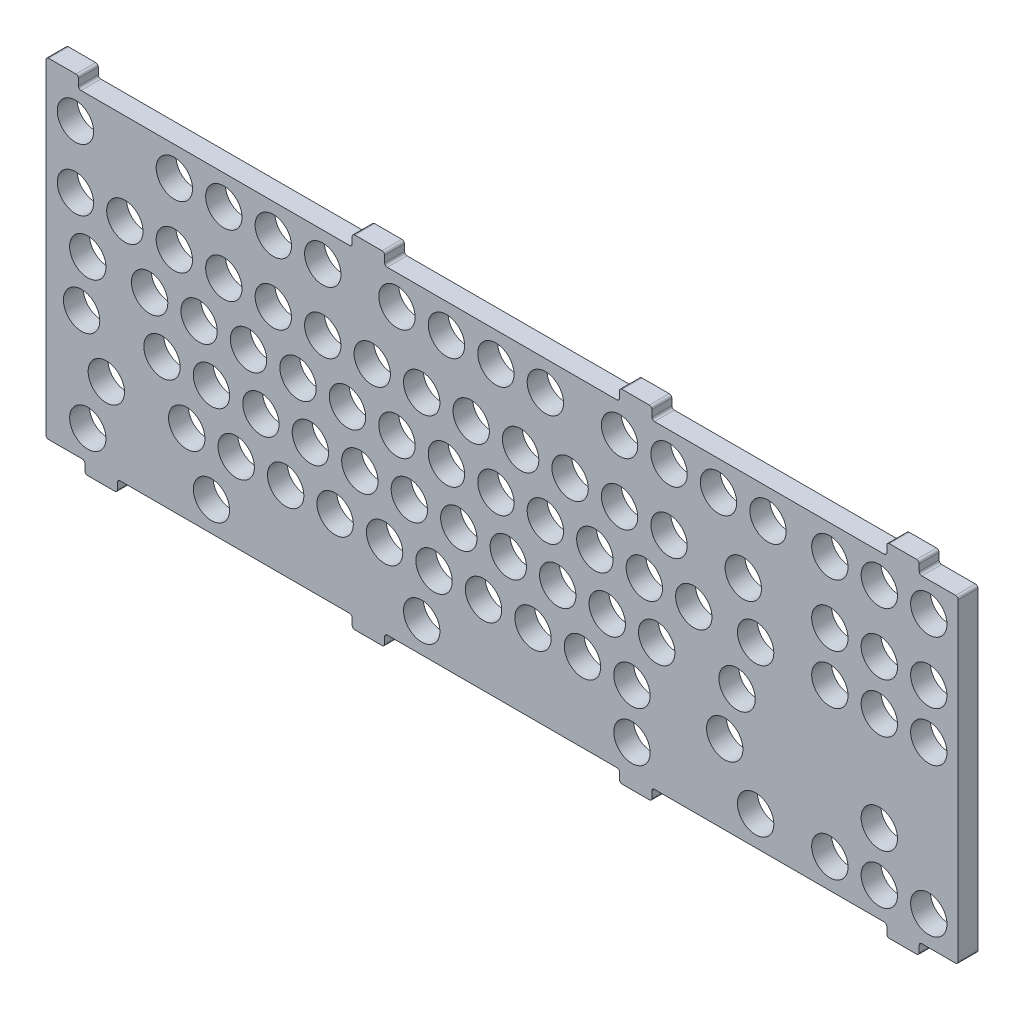
SolidWorks part; units mm, degrees
ref_plane "Front Plane" through (0, 0, 0) normal (0, 0, 1) x (1, 0, 0)
ref_plane "Top Plane" through (0, 0, 0) normal (0, 1, 0) x (1, 0, 0)
ref_plane "Right Plane" through (0, 0, 0) normal (1, 0, 0) x (0, 0, -1)
sketch "Sketch1" plane through (0, 0, 0) normal (0, 0, 1) x (1, 0, 0)
  line L0 (-164.1313, 65.8312) -> (-174.6313, 65.8312)
  line L1 (-163.1313, 62.3312) -> (-163.1312, 64.8312)
  line L2 (-58.7104, 61.3312) -> (-162.1313, 61.3312)
  line L3 (-57.7104, 64.8312) -> (-57.7104, 62.3312)
  line L4 (-45.2104, 62.3312) -> (-45.2104, 64.8312)
  line L5 (44.2104, 61.3312) -> (-44.2104, 61.3312)
  line L6 (45.2104, 64.8312) -> (45.2104, 62.3312)
  line L7 (56.7104, 65.8312) -> (46.2104, 65.8312)
  line L8 (57.7104, 62.3312) -> (57.7104, 64.8312)
  line L9 (147.1312, 61.3312) -> (58.7104, 61.3312)
  line L10 (148.1312, 64.8312) -> (148.1312, 62.3312)
  line L11 (159.6312, 65.8312) -> (149.1312, 65.8312)
  line L12 (160.6312, 62.3312) -> (160.6312, 64.8312)
  line L13 (174.6313, 61.3312) -> (161.6312, 61.3312)
  line L14 (175.6313, -60.3312) -> (175.6313, 60.3312)
  line L15 (161.6312, -61.3312) -> (174.6313, -61.3312)
  line L16 (160.6312, -64.8312) -> (160.6312, -62.3312)
  line L17 (149.1312, -65.8312) -> (159.6312, -65.8312)
  line L18 (148.1312, -62.3312) -> (148.1312, -64.8312)
  line L19 (58.7104, -61.3312) -> (147.1312, -61.3312)
  line L20 (57.7104, -64.8312) -> (57.7104, -62.3312)
  line L21 (46.2104, -65.8312) -> (56.7104, -65.8312)
  line L22 (45.2104, -62.3312) -> (45.2104, -64.8312)
  line L23 (-44.2104, -61.3312) -> (44.2104, -61.3312)
  line L24 (-45.2104, -64.8312) -> (-45.2104, -62.3312)
  line L25 (-56.7104, -65.8312) -> (-46.2104, -65.8312)
  line L26 (-57.7104, -62.3312) -> (-57.7104, -64.8312)
  line L27 (-147.1313, -61.3312) -> (-58.7104, -61.3312)
  line L28 (-148.1313, -64.8312) -> (-148.1313, -62.3312)
  line L29 (-159.6313, -65.8312) -> (-149.1313, -65.8312)
  line L30 (-160.6313, -62.3312) -> (-160.6313, -64.8312)
  line L31 (-174.6313, -61.3312) -> (-161.6313, -61.3312)
  line L32 (-175.6313, 64.8312) -> (-175.6313, -60.3312)
  line L33 (-46.2104, 65.8312) -> (-56.7104, 65.8312)
  arc A0 (-163.1312, 64.8312) -> (-164.1313, 65.8312) centre (-164.1313, 64.8312) ccw
  arc A1 (-163.1313, 62.3312) -> (-162.1313, 61.3312) centre (-162.1313, 62.3312) ccw
  arc A2 (-58.7104, 61.3312) -> (-57.7104, 62.3312) centre (-58.7104, 62.3312) ccw
  arc A3 (-56.7104, 65.8312) -> (-57.7104, 64.8312) centre (-56.7104, 64.8312) ccw
  arc A4 (-45.2104, 64.8312) -> (-46.2104, 65.8312) centre (-46.2104, 64.8312) ccw
  arc A5 (-45.2104, 62.3312) -> (-44.2104, 61.3312) centre (-44.2104, 62.3312) ccw
  arc A6 (44.2104, 61.3312) -> (45.2104, 62.3312) centre (44.2104, 62.3312) ccw
  arc A7 (46.2104, 65.8312) -> (45.2104, 64.8312) centre (46.2104, 64.8312) ccw
  arc A8 (57.7104, 64.8312) -> (56.7104, 65.8312) centre (56.7104, 64.8312) ccw
  arc A9 (57.7104, 62.3312) -> (58.7104, 61.3312) centre (58.7104, 62.3312) ccw
  arc A10 (147.1312, 61.3312) -> (148.1312, 62.3312) centre (147.1312, 62.3312) ccw
  arc A11 (149.1312, 65.8312) -> (148.1312, 64.8312) centre (149.1312, 64.8312) ccw
  arc A12 (160.6312, 62.3312) -> (161.6312, 61.3312) centre (161.6312, 62.3312) ccw
  arc A13 (175.6313, 60.3312) -> (174.6313, 61.3312) centre (174.6313, 60.3312) ccw
  arc A14 (174.6313, -61.3312) -> (175.6313, -60.3312) centre (174.6313, -60.3312) ccw
  arc A15 (161.6312, -61.3312) -> (160.6312, -62.3312) centre (161.6312, -62.3312) ccw
  arc A16 (159.6312, -65.8312) -> (160.6312, -64.8312) centre (159.6312, -64.8312) ccw
  arc A17 (148.1312, -64.8312) -> (149.1312, -65.8312) centre (149.1312, -64.8312) ccw
  arc A18 (148.1312, -62.3312) -> (147.1312, -61.3312) centre (147.1312, -62.3312) ccw
  arc A19 (58.7104, -61.3312) -> (57.7104, -62.3312) centre (58.7104, -62.3312) ccw
  arc A20 (56.7104, -65.8312) -> (57.7104, -64.8312) centre (56.7104, -64.8312) ccw
  arc A21 (45.2104, -64.8312) -> (46.2104, -65.8312) centre (46.2104, -64.8312) ccw
  arc A22 (45.2104, -62.3312) -> (44.2104, -61.3312) centre (44.2104, -62.3312) ccw
  arc A23 (-44.2104, -61.3312) -> (-45.2104, -62.3312) centre (-44.2104, -62.3312) ccw
  arc A24 (-46.2104, -65.8312) -> (-45.2104, -64.8312) centre (-46.2104, -64.8312) ccw
  arc A25 (-57.7104, -64.8312) -> (-56.7104, -65.8312) centre (-56.7104, -64.8312) ccw
  arc A26 (-57.7104, -62.3312) -> (-58.7104, -61.3312) centre (-58.7104, -62.3312) ccw
  arc A27 (-147.1313, -61.3312) -> (-148.1313, -62.3312) centre (-147.1313, -62.3312) ccw
  arc A28 (-149.1313, -65.8312) -> (-148.1313, -64.8312) centre (-149.1313, -64.8312) ccw
  arc A29 (-160.6313, -64.8312) -> (-159.6313, -65.8312) centre (-159.6313, -64.8312) ccw
  arc A30 (-160.6313, -62.3312) -> (-161.6313, -61.3312) centre (-161.6313, -62.3312) ccw
  arc A31 (-175.6313, -60.3312) -> (-174.6313, -61.3312) centre (-174.6313, -60.3312) ccw
  arc A32 (-174.6313, 65.8312) -> (-175.6313, 64.8312) centre (-174.6313, 64.8312) ccw
  arc A33 (11.9069, -37.9562) -> (11.9069, -23.9554) centre (11.9069, -30.9558) ccw
  arc A34 (11.9069, -23.9554) -> (11.9069, -37.9562) centre (11.9069, -30.9558) ccw
  arc A35 (50.0069, -57.0062) -> (50.0069, -43.0054) centre (50.0069, -50.0058) ccw
  arc A36 (50.0069, -43.0054) -> (50.0069, -57.0062) centre (50.0069, -50.0058) ccw
  arc A37 (40.4819, -18.906) -> (40.4819, -4.9054) centre (40.4819, -11.9057) ccw
  arc A38 (40.4819, -4.9054) -> (40.4819, -18.906) centre (40.4819, -11.9057) ccw
  arc A39 (2.3819, -18.906) -> (2.3819, -4.9054) centre (2.3819, -11.9057) ccw
  arc A40 (2.3819, -4.9054) -> (2.3819, -18.906) centre (2.3819, -11.9057) ccw
  arc A41 (-35.7196, -18.906) -> (-35.7196, -4.9054) centre (-35.7196, -11.9057) ccw
  arc A42 (-35.7196, -4.9054) -> (-35.7196, -18.906) centre (-35.7196, -11.9057) ccw
  arc A43 (-45.2431, -37.9562) -> (-45.2431, -23.9554) centre (-45.2431, -30.9558) ccw
  arc A44 (-45.2431, -23.9554) -> (-45.2431, -37.9562) centre (-45.2431, -30.9558) ccw
  arc A45 (-54.7696, -18.906) -> (-54.7696, -4.9054) centre (-54.7696, -11.9057) ccw
  arc A46 (-54.7696, -4.9054) -> (-54.7696, -18.906) centre (-54.7696, -11.9057) ccw
  arc A47 (-64.2946, -37.9562) -> (-64.2946, -23.9554) centre (-64.2946, -30.9558) ccw
  arc A48 (-64.2946, -23.9554) -> (-64.2946, -37.9562) centre (-64.2946, -30.9558) ccw
  arc A49 (-102.3933, -37.9562) -> (-102.3933, -23.9554) centre (-102.3933, -30.9558) ccw
  arc A50 (-102.3933, -23.9554) -> (-102.3933, -37.9562) centre (-102.3933, -30.9558) ccw
  arc A51 (-111.9197, -18.906) -> (-111.9197, -4.9054) centre (-111.9197, -11.9057) ccw
  arc A52 (-111.9197, -4.9054) -> (-111.9197, -18.906) centre (-111.9197, -11.9057) ccw
  arc A53 (-121.4433, -37.9562) -> (-121.4433, -23.9554) centre (-121.4433, -30.9558) ccw
  arc A54 (-121.4433, -23.9554) -> (-121.4433, -37.9562) centre (-121.4433, -30.9558) ccw
  arc A55 (-159.5432, -57.0062) -> (-159.5432, -43.0054) centre (-159.5432, -50.0058) ccw
  arc A56 (-159.5432, -43.0054) -> (-159.5432, -57.0062) centre (-159.5432, -50.0058) ccw
  arc A57 (-161.9252, -18.906) -> (-161.9252, -4.9054) centre (-161.9252, -11.9057) ccw
  arc A58 (-161.9252, -4.9054) -> (-161.9252, -18.906) centre (-161.9252, -11.9057) ccw
  arc A59 (90.4879, -18.906) -> (90.4879, -4.9054) centre (90.4879, -11.9057) ccw
  arc A60 (90.4879, -4.9054) -> (90.4879, -18.906) centre (90.4879, -11.9057) ccw
  arc A61 (97.6319, -57.0062) -> (97.6319, -43.0054) centre (97.6319, -50.0058) ccw
  arc A62 (97.6319, -43.0054) -> (97.6319, -57.0062) centre (97.6319, -50.0058) ccw
  arc A63 (145.2569, -37.9562) -> (145.2569, -23.9554) centre (145.2569, -30.9558) ccw
  arc A64 (145.2569, -23.9554) -> (145.2569, -37.9562) centre (145.2569, -30.9558) ccw
  arc A65 (145.2569, -57.0062) -> (145.2569, -43.0054) centre (145.2569, -50.0058) ccw
  arc A66 (145.2569, -43.0054) -> (145.2569, -57.0062) centre (145.2569, -50.0058) ccw
  arc A67 (145.2569, 0.144) -> (145.2569, 14.1446) centre (145.2569, 7.1443) ccw
  arc A68 (145.2569, 14.1446) -> (145.2569, 0.144) centre (145.2569, 7.1443) ccw
  arc A69 (97.6319, 0.144) -> (97.6319, 14.1446) centre (97.6319, 7.1443) ccw
  arc A70 (97.6319, 14.1446) -> (97.6319, 0.144) centre (97.6319, 7.1443) ccw
  arc A71 (126.2069, 19.194) -> (126.2069, 33.1946) centre (126.2069, 26.1943) ccw
  arc A72 (126.2069, 33.1946) -> (126.2069, 19.194) centre (126.2069, 26.1943) ccw
  arc A73 (164.3069, 19.194) -> (164.3069, 33.1946) centre (164.3069, 26.1943) ccw
  arc A74 (164.3069, 33.1946) -> (164.3069, 19.194) centre (164.3069, 26.1943) ccw
  arc A75 (145.2569, 43.0062) -> (145.2569, 57.0062) centre (145.2569, 50.0062) ccw
  arc A76 (145.2569, 57.0062) -> (145.2569, 43.0062) centre (145.2569, 50.0062) ccw
  arc A77 (102.3934, 43.0062) -> (102.3934, 57.0062) centre (102.3934, 50.0062) ccw
  arc A78 (102.3934, 57.0062) -> (102.3934, 43.0062) centre (102.3934, 50.0062) ccw
  arc A79 (73.8184, 0.144) -> (73.8184, 14.1446) centre (73.8184, 7.1443) ccw
  arc A80 (73.8184, 14.1446) -> (73.8184, 0.144) centre (73.8184, 7.1443) ccw
  arc A81 (35.7184, 0.1315) -> (35.7184, 14.1571) centre (35.7184, 7.1443) ccw
  arc A82 (35.7184, 14.1571) -> (35.7184, 0.1315) centre (35.7184, 7.1443) ccw
  arc A83 (-2.3816, 0.144) -> (-2.3816, 14.1446) centre (-2.3816, 7.1443) ccw
  arc A84 (-2.3816, 14.1446) -> (-2.3816, 0.144) centre (-2.3816, 7.1443) ccw
  arc A85 (26.1934, 19.194) -> (26.1934, 33.1946) centre (26.1934, 26.1943) ccw
  arc A86 (26.1934, 33.1946) -> (26.1934, 19.194) centre (26.1934, 26.1943) ccw
  arc A87 (64.2934, 19.194) -> (64.2934, 33.1946) centre (64.2934, 26.1943) ccw
  arc A88 (64.2934, 33.1946) -> (64.2934, 19.194) centre (64.2934, 26.1943) ccw
  arc A89 (45.2434, 43.0062) -> (45.2434, 57.0062) centre (45.2434, 50.0062) ccw
  arc A90 (45.2434, 57.0062) -> (45.2434, 43.0062) centre (45.2434, 50.0062) ccw
  arc A91 (-2.3816, 43.0062) -> (-2.3816, 57.0062) centre (-2.3816, 50.0062) ccw
  arc A92 (-2.3816, 57.0062) -> (-2.3816, 43.0062) centre (-2.3816, 50.0062) ccw
  arc A93 (-159.5432, 0.144) -> (-159.5432, 14.1446) centre (-159.5432, 7.1443) ccw
  arc A94 (-159.5432, 14.1446) -> (-159.5432, 0.144) centre (-159.5432, 7.1443) ccw
  arc A95 (-21.4316, 0.144) -> (-21.4316, 14.1446) centre (-21.4316, 7.1443) ccw
  arc A96 (-21.4316, 14.1446) -> (-21.4316, 0.144) centre (-21.4316, 7.1443) ccw
  arc A97 (-59.5316, 0.144) -> (-59.5316, 14.1446) centre (-59.5316, 7.1443) ccw
  arc A98 (-59.5316, 14.1446) -> (-59.5316, 0.144) centre (-59.5316, 7.1443) ccw
  arc A99 (-97.6315, 0.144) -> (-97.6315, 14.1446) centre (-97.6315, 7.1443) ccw
  arc A100 (-97.6315, 14.1446) -> (-97.6315, 0.144) centre (-97.6315, 7.1443) ccw
  arc A101 (-135.7315, 0.144) -> (-135.7315, 14.1446) centre (-135.7315, 7.1443) ccw
  arc A102 (-135.7315, 14.1446) -> (-135.7315, 0.144) centre (-135.7315, 7.1443) ccw
  arc A103 (-50.0066, 19.194) -> (-50.0066, 33.1946) centre (-50.0066, 26.1943) ccw
  arc A104 (-50.0066, 33.1946) -> (-50.0066, 19.194) centre (-50.0066, 26.1943) ccw
  arc A105 (-88.1065, 19.194) -> (-88.1065, 33.1946) centre (-88.1065, 26.1943) ccw
  arc A106 (-88.1065, 33.1946) -> (-88.1065, 19.194) centre (-88.1065, 26.1943) ccw
  arc A107 (-126.2065, 19.194) -> (-126.2065, 33.1946) centre (-126.2065, 26.1943) ccw
  arc A108 (-126.2065, 33.1946) -> (-126.2065, 19.194) centre (-126.2065, 26.1943) ccw
  arc A109 (-21.4316, 43.0062) -> (-21.4316, 57.0062) centre (-21.4316, 50.0062) ccw
  arc A110 (-21.4316, 57.0062) -> (-21.4316, 43.0062) centre (-21.4316, 50.0062) ccw
  arc A111 (-69.0565, 43.0062) -> (-69.0565, 57.0062) centre (-69.0565, 50.0062) ccw
  arc A112 (-69.0565, 57.0062) -> (-69.0565, 43.0062) centre (-69.0565, 50.0062) ccw
  arc A113 (-107.1565, 43.0062) -> (-107.1565, 57.0062) centre (-107.1565, 50.0062) ccw
  arc A114 (-107.1565, 57.0062) -> (-107.1565, 43.0062) centre (-107.1565, 50.0062) ccw
  arc A115 (-164.3064, 43.0062) -> (-164.3064, 57.0062) centre (-164.3064, 50.0062) ccw
  arc A116 (-164.3064, 57.0062) -> (-164.3064, 43.0062) centre (-164.3064, 50.0062) ccw
  arc A117 (-126.2065, 43.0062) -> (-126.2065, 57.0062) centre (-126.2065, 50.0062) ccw
  arc A118 (-126.2065, 57.0062) -> (-126.2065, 43.0062) centre (-126.2065, 50.0062) ccw
  arc A119 (-88.1065, 43.0062) -> (-88.1065, 57.0062) centre (-88.1065, 50.0062) ccw
  arc A120 (-88.1065, 57.0062) -> (-88.1065, 43.0062) centre (-88.1065, 50.0062) ccw
  arc A121 (-40.4816, 43.0062) -> (-40.4816, 57.0062) centre (-40.4816, 50.0062) ccw
  arc A122 (-40.4816, 57.0062) -> (-40.4816, 43.0062) centre (-40.4816, 50.0062) ccw
  arc A123 (-145.2565, 19.194) -> (-145.2565, 33.1946) centre (-145.2565, 26.1943) ccw
  arc A124 (-145.2565, 33.1946) -> (-145.2565, 19.194) centre (-145.2565, 26.1943) ccw
  arc A125 (-107.1565, 19.194) -> (-107.1565, 33.1946) centre (-107.1565, 26.1943) ccw
  arc A126 (-107.1565, 33.1946) -> (-107.1565, 19.194) centre (-107.1565, 26.1943) ccw
  arc A127 (-69.0565, 19.194) -> (-69.0565, 33.1946) centre (-69.0565, 26.1943) ccw
  arc A128 (-69.0565, 33.1946) -> (-69.0565, 19.194) centre (-69.0565, 26.1943) ccw
  arc A129 (-30.9566, 19.194) -> (-30.9566, 33.1946) centre (-30.9566, 26.1943) ccw
  arc A130 (-30.9566, 33.1946) -> (-30.9566, 19.194) centre (-30.9566, 26.1943) ccw
  arc A131 (-116.6815, 0.144) -> (-116.6815, 14.1446) centre (-116.6815, 7.1443) ccw
  arc A132 (-116.6815, 14.1446) -> (-116.6815, 0.144) centre (-116.6815, 7.1443) ccw
  arc A133 (-78.5815, 0.144) -> (-78.5815, 14.1446) centre (-78.5815, 7.1443) ccw
  arc A134 (-78.5815, 14.1446) -> (-78.5815, 0.144) centre (-78.5815, 7.1443) ccw
  arc A135 (-40.4816, 0.144) -> (-40.4816, 14.1446) centre (-40.4816, 7.1443) ccw
  arc A136 (-40.4816, 14.1446) -> (-40.4816, 0.144) centre (-40.4816, 7.1443) ccw
  arc A137 (-164.3064, 19.194) -> (-164.3064, 33.1946) centre (-164.3064, 26.1943) ccw
  arc A138 (-164.3064, 33.1946) -> (-164.3064, 19.194) centre (-164.3064, 26.1943) ccw
  arc A139 (-11.9066, 19.194) -> (-11.9066, 33.1946) centre (-11.9066, 26.1943) ccw
  arc A140 (-11.9066, 33.1946) -> (-11.9066, 19.194) centre (-11.9066, 26.1943) ccw
  arc A141 (16.6684, 43.0062) -> (16.6684, 57.0062) centre (16.6684, 50.0062) ccw
  arc A142 (16.6684, 57.0062) -> (16.6684, 43.0062) centre (16.6684, 50.0062) ccw
  arc A143 (64.2934, 43.0062) -> (64.2934, 57.0062) centre (64.2934, 50.0062) ccw
  arc A144 (64.2934, 57.0062) -> (64.2934, 43.0062) centre (64.2934, 50.0062) ccw
  arc A145 (45.2434, 19.194) -> (45.2434, 33.1946) centre (45.2434, 26.1943) ccw
  arc A146 (45.2434, 33.1946) -> (45.2434, 19.194) centre (45.2434, 26.1943) ccw
  arc A147 (7.1434, 19.194) -> (7.1434, 33.1946) centre (7.1434, 26.1943) ccw
  arc A148 (7.1434, 33.1946) -> (7.1434, 19.194) centre (7.1434, 26.1943) ccw
  arc A149 (16.6684, 0.144) -> (16.6684, 14.1446) centre (16.6684, 7.1443) ccw
  arc A150 (16.6684, 14.1446) -> (16.6684, 0.144) centre (16.6684, 7.1443) ccw
  arc A151 (54.7684, 0.144) -> (54.7684, 14.1446) centre (54.7684, 7.1443) ccw
  arc A152 (54.7684, 14.1446) -> (54.7684, 0.144) centre (54.7684, 7.1443) ccw
  arc A153 (83.3434, 43.0062) -> (83.3434, 57.0062) centre (83.3434, 50.0062) ccw
  arc A154 (83.3434, 57.0062) -> (83.3434, 43.0062) centre (83.3434, 50.0062) ccw
  arc A155 (126.2069, 43.0062) -> (126.2069, 57.0062) centre (126.2069, 50.0062) ccw
  arc A156 (126.2069, 57.0062) -> (126.2069, 43.0062) centre (126.2069, 50.0062) ccw
  arc A157 (164.3069, 43.0062) -> (164.3069, 57.0062) centre (164.3069, 50.0062) ccw
  arc A158 (164.3069, 57.0062) -> (164.3069, 43.0062) centre (164.3069, 50.0062) ccw
  arc A159 (145.2569, 19.194) -> (145.2569, 33.1946) centre (145.2569, 26.1943) ccw
  arc A160 (145.2569, 33.1946) -> (145.2569, 19.194) centre (145.2569, 26.1943) ccw
  arc A161 (92.8684, 19.194) -> (92.8684, 33.1946) centre (92.8684, 26.1943) ccw
  arc A162 (92.8684, 33.1946) -> (92.8684, 19.194) centre (92.8684, 26.1943) ccw
  arc A163 (126.2069, 0.144) -> (126.2069, 14.1446) centre (126.2069, 7.1443) ccw
  arc A164 (126.2069, 14.1446) -> (126.2069, 0.144) centre (126.2069, 7.1443) ccw
  arc A165 (164.3069, 0.144) -> (164.3069, 14.1446) centre (164.3069, 7.1443) ccw
  arc A166 (164.3069, 14.1446) -> (164.3069, 0.144) centre (164.3069, 7.1443) ccw
  arc A167 (126.2069, -57.0062) -> (126.2069, -43.0054) centre (126.2069, -50.0058) ccw
  arc A168 (126.2069, -43.0054) -> (126.2069, -57.0062) centre (126.2069, -50.0058) ccw
  arc A169 (164.3069, -57.0062) -> (164.3069, -43.0054) centre (164.3069, -50.0058) ccw
  arc A170 (164.3069, -43.0054) -> (164.3069, -57.0062) centre (164.3069, -50.0058) ccw
  arc A171 (85.7249, -37.9562) -> (85.7249, -23.9554) centre (85.7249, -30.9558) ccw
  arc A172 (85.7249, -23.9554) -> (85.7249, -37.9562) centre (85.7249, -30.9558) ccw
  arc A173 (59.5319, -18.906) -> (59.5319, -4.9054) centre (59.5319, -11.9057) ccw
  arc A174 (59.5319, -4.9054) -> (59.5319, -18.906) centre (59.5319, -11.9057) ccw
  arc A175 (-130.9697, -18.906) -> (-130.9697, -4.9054) centre (-130.9697, -11.9057) ccw
  arc A176 (-130.9697, -4.9054) -> (-130.9697, -18.906) centre (-130.9697, -11.9057) ccw
  arc A177 (-152.4002, -37.9562) -> (-152.4002, -23.9554) centre (-152.4002, -30.9558) ccw
  arc A178 (-152.4002, -23.9554) -> (-152.4002, -37.9562) centre (-152.4002, -30.9558) ccw
  arc A179 (-111.9183, -57.0062) -> (-111.9183, -43.0054) centre (-111.9183, -50.0058) ccw
  arc A180 (-111.9183, -43.0054) -> (-111.9183, -57.0062) centre (-111.9183, -50.0058) ccw
  arc A181 (-92.8697, -18.906) -> (-92.8697, -4.9054) centre (-92.8697, -11.9057) ccw
  arc A182 (-92.8697, -4.9054) -> (-92.8697, -18.906) centre (-92.8697, -11.9057) ccw
  arc A183 (-83.3447, -37.9562) -> (-83.3447, -23.9554) centre (-83.3447, -30.9558) ccw
  arc A184 (-83.3447, -23.9554) -> (-83.3447, -37.9562) centre (-83.3447, -30.9558) ccw
  arc A185 (-73.8197, -18.906) -> (-73.8197, -4.9054) centre (-73.8197, -11.9057) ccw
  arc A186 (-73.8197, -4.9054) -> (-73.8197, -18.906) centre (-73.8197, -11.9057) ccw
  arc A187 (-30.9566, -57.0062) -> (-30.9566, -43.0054) centre (-30.9566, -50.0058) ccw
  arc A188 (-30.9566, -43.0054) -> (-30.9566, -57.0062) centre (-30.9566, -50.0058) ccw
  arc A189 (-26.1931, -37.9562) -> (-26.1931, -23.9554) centre (-26.1931, -30.9558) ccw
  arc A190 (-26.1931, -23.9554) -> (-26.1931, -37.9562) centre (-26.1931, -30.9558) ccw
  arc A191 (-16.6696, -18.906) -> (-16.6696, -4.9054) centre (-16.6696, -11.9057) ccw
  arc A192 (-16.6696, -4.9054) -> (-16.6696, -18.906) centre (-16.6696, -11.9057) ccw
  arc A193 (21.4319, -18.906) -> (21.4319, -4.9054) centre (21.4319, -11.9057) ccw
  arc A194 (21.4319, -4.9054) -> (21.4319, -18.906) centre (21.4319, -11.9057) ccw
  arc A195 (50.0069, -37.9562) -> (50.0069, -23.9554) centre (50.0069, -30.9558) ccw
  arc A196 (50.0069, -23.9554) -> (50.0069, -37.9562) centre (50.0069, -30.9558) ccw
  arc A197 (30.9569, -37.9562) -> (30.9569, -23.9554) centre (30.9569, -30.9558) ccw
  arc A198 (30.9569, -23.9554) -> (30.9569, -37.9562) centre (30.9569, -30.9558) ccw
  arc A199 (-7.1431, -37.9562) -> (-7.1431, -23.9554) centre (-7.1431, -30.9558) ccw
  arc A200 (-7.1431, -23.9554) -> (-7.1431, -37.9562) centre (-7.1431, -30.9558) ccw
  arc A201 (160.6312, 64.8312) -> (159.6312, 65.8312) centre (159.6312, 64.8312) ccw
extrude "Boss-Extrude1" add sketch "Sketch1" along normal blind 7.63
